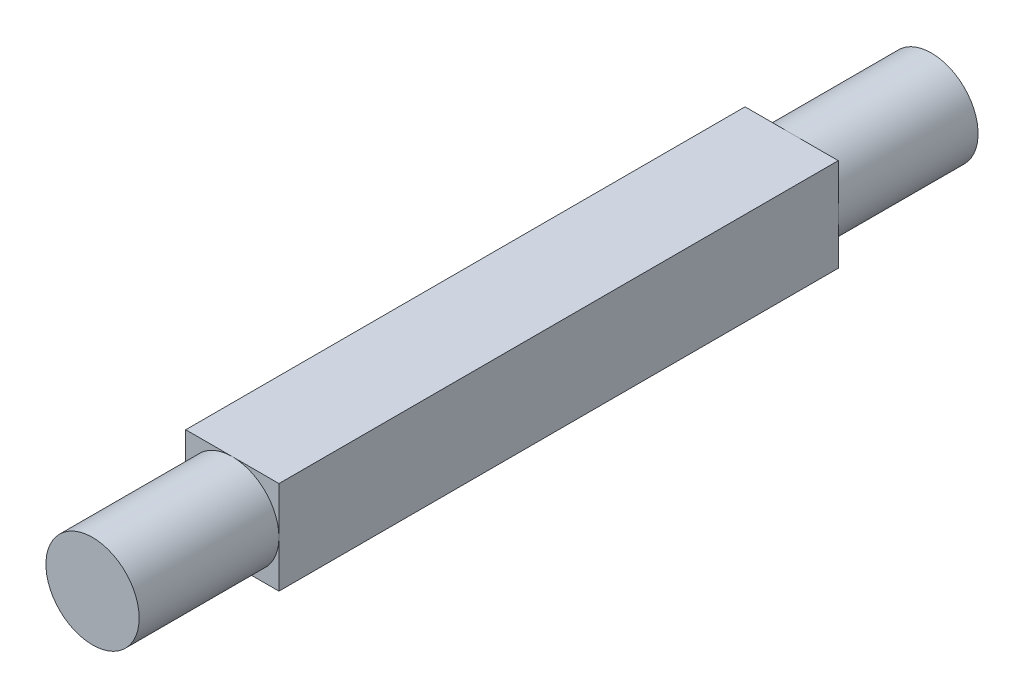
SolidWorks part; units mm, degrees
ref_plane "Спереди" through (0, 0, 0) normal (0, 0, 1) x (1, 0, 0)
ref_plane "Сверху" through (0, 0, 0) normal (0, 1, 0) x (1, 0, 0)
ref_plane "Справа" through (0, 0, 0) normal (1, 0, 0) x (0, 0, -1)
sketch "Эскиз1" plane through (0, 0, 0) normal (0, 0, 1) x (1, 0, 0)
  line L1 (1, -1) -> (-1, -1)
  line L2 (1, -1) -> (1, 1)
  line L3 (1, 1) -> (-1, 1)
  line L4 (-1, -1) -> (-1, 1)
  line L5 (1, -1) -> (-1, 1) construction
  line L6 (1, 1) -> (-1, -1) construction
  point P0 (0, 0)
  dimension "D1" = 2
  dimension "D2" = 2
extrude "Бобышка-Вытянуть1" add sketch "Эскиз1" along normal blind 12
sketch "Эскиз2" plane through (0, 0, 12) normal (0, 0, 1) x (1, 0, 0)
  circle A0 centre (0, 0) radius 1
extrude "Бобышка-Вытянуть2" add sketch "Эскиз2" along normal blind 3
sketch "Эскиз3" plane through (0, 0, 0) normal (0, 0, -1) x (-1, 0, 0)
  circle A0 centre (0, 0) radius 1
extrude "Бобышка-Вытянуть3" add sketch "Эскиз3" along normal blind 3
